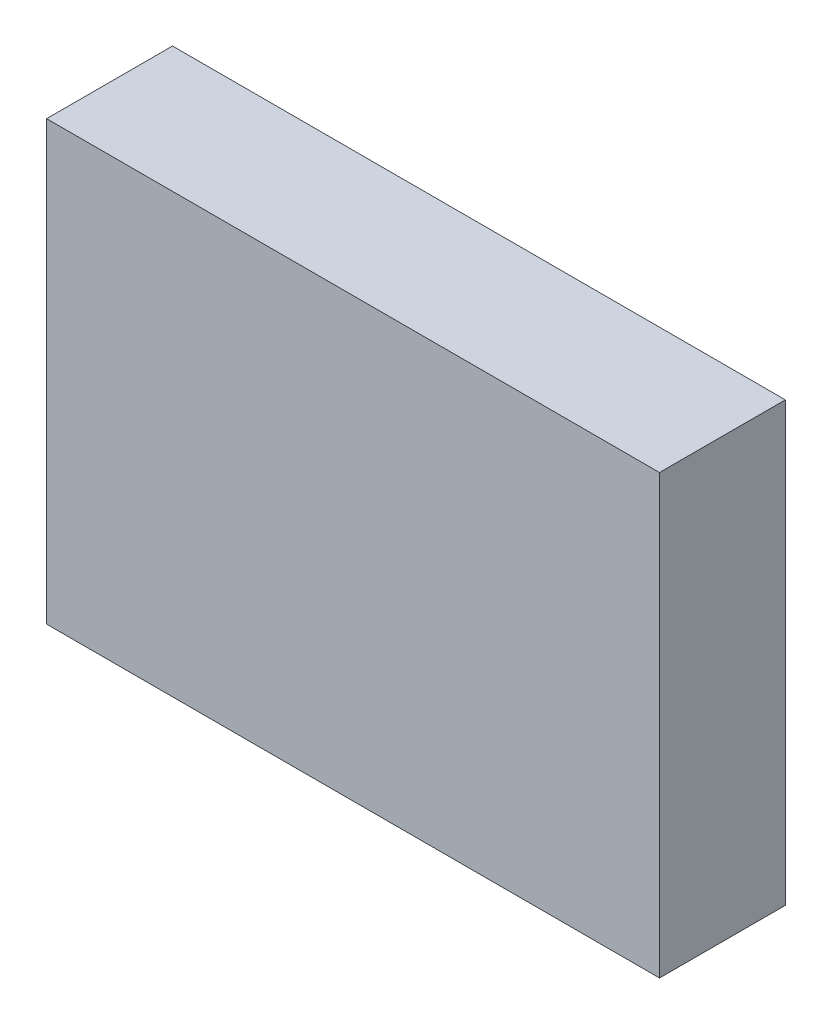
SolidWorks part; units mm, degrees
ref_plane "Front Plane" through (0, 0, 0) normal (0, 0, 1) x (1, 0, 0)
ref_plane "Top Plane" through (0, 0, 0) normal (0, 1, 0) x (1, 0, 0)
ref_plane "Right Plane" through (0, 0, 0) normal (1, 0, 0) x (0, 0, -1)
sketch "Sketch1" plane through (0, 0, 0) normal (0, 0, 1) x (1, 0, 0)
  line L1 (-44.45, -31.75) -> (44.45, -31.75)
  line L2 (-44.45, -31.75) -> (-44.45, 31.75)
  line L3 (-44.45, 31.75) -> (44.45, 31.75)
  line L4 (44.45, -31.75) -> (44.45, 31.75)
  line L5 (-44.45, -31.75) -> (44.45, 31.75) construction
  line L6 (-44.45, 31.75) -> (44.45, -31.75) construction
  point P0 (0, 0)
  dimension "D1" = 88.9
  dimension "D2" = 63.5
extrude "Boss-Extrude1" add sketch "Sketch1" along normal mid plane 18.2562
